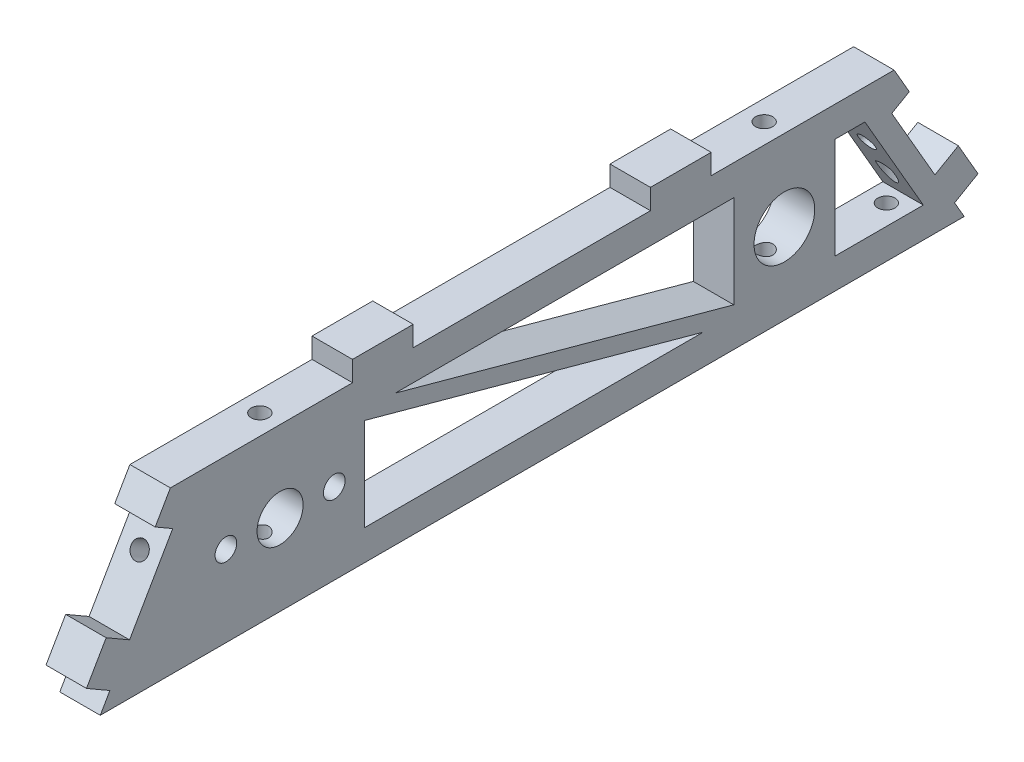
SolidWorks part; units mm, degrees
material "6061-T6 (SS)"
ref_plane "Front Plane" through (0, 0, 0) normal (0, 0, 1) x (1, 0, 0)
ref_plane "Top Plane" through (0, 0, 0) normal (0, 1, 0) x (1, 0, 0)
ref_plane "Right Plane" through (0, 0, 0) normal (1, 0, 0) x (0, 0, -1)
sketch "Sketch1" plane through (0, 0, 0) normal (1, 0, 0) x (0, 0, -1)
  line L0 (0, 0) -> (-14.6647, 25.4)
  line L1 (0, 0) -> (-142.875, 0)
  line L3 (-14.6647, 25.4) -> (-128.2103, 25.4)
  line L5 (-142.875, 0) -> (-128.2103, 25.4)
  circle A0 centre (-110.998, 12.7) radius 3.6195
  circle A1 centre (-31.877, 12.7) radius 4.7625
  circle A2 centre (-102.498, 12.7) radius 1.7
  circle A3 centre (-119.498, 12.7) radius 1.7
  dimension "D3" = 7.239
  dimension "D5" = 9.525
  dimension "D9" = 3.4
  dimension "D2" = 25.4
  dimension "D4" = 12.7
  dimension "D6" = 142.875
  dimension "D7" = 31.877
  dimension "D8" = 12.7
  dimension "D10" = 8.5
  dimension "D11" = 8.5
  dimension "D13" = 60
  dimension "D14" = 60
  dimension "D15" = 31.877
extrude "Boss-Extrude1" add sketch "Sketch1" along normal blind 6.35
sketch "Sketch12" plane through (0, 0, 0) normal (0, 0.5, -0.866) x (-1, 0, 0)
  line L0 (-6.35, 0) -> (-6.35, 29.3294) construction
  line L1 (-6.35, 11.0236) -> (0, 11.0236)
  line L2 (-6.35, 11.0236) -> (-6.35, 4.8514)
  line L3 (-6.35, 4.8514) -> (0, 4.8514)
  line L4 (0, 11.0236) -> (0, 4.8514)
  line L5 (0, 0) -> (0, 29.3294) construction
  line L6 (0, 7.9375) -> (-6.35, 7.9375) construction
  line L8 (-6.35, 0) -> (0, 0) construction
  point P8 (0, 7.9375)
  dimension "D1" = 6.1722
  dimension "D2" = 7.9375
extrude "Boss-Extrude3" add sketch "Sketch12" along normal blind 1.0668
sketch "Sketch19" plane through (0, 0, 0) normal (-1, 0, 0) x (0, 0, 1)
  line L0 (14.6647, 25.4) -> (128.2103, 25.4) construction
  line L1 (39.8145, 20.6375) -> (97.7355, 20.6375)
  line L2 (39.8145, 20.6375) -> (39.8145, 4.7625)
  line L3 (39.8145, 4.7625) -> (97.7355, 4.7625)
  line L4 (97.7355, 20.6375) -> (97.7355, 4.7625)
  line L5 (142.875, 0) -> (0, 0) construction
  line L6 (39.8145, 4.7625) -> (97.7355, 20.6375) construction
  line L7 (44.6191, 4.7625) -> (97.7355, 19.3207)
  line L8 (39.8145, 6.0793) -> (92.9309, 20.6375)
  line L9 (39.4788, 5.9873) -> (97.3998, 21.8623) construction
  line L10 (40.1502, 3.5377) -> (98.0712, 19.4127) construction
  line L11 (10.082, 4.7625) -> (19.2474, 20.6375)
  line L12 (23.9395, 20.6375) -> (23.9395, 4.7625)
  line L13 (23.9395, 4.7625) -> (10.082, 4.7625)
  line L14 (5.5118, 9.5467) -> (14.6647, 25.4) construction
  line L15 (23.9395, 20.6375) -> (19.2474, 20.6375)
  circle A0 centre (31.877, 12.7) radius 4.7625 construction
  circle A1 centre (102.498, 12.7) radius 1.7 construction
  dimension "D1" = 4.7625
  dimension "D2" = 4.7625
  dimension "D3" = 7.9375
  dimension "D4" = 4.7625
  dimension "D7" = 6.35
  dimension "D8" = 7.9375
  dimension "D9" = 4.7625
  dimension "D5" = 1.27
  dimension "D6" = 1.27
extrude "Cut-Extrude1" cut sketch "Sketch19" against normal through all contours L2 L8 L1 | L7 L3 L4 | L12 L15 L11 L13
hole_wizard "Tap Drill for #6-32 Tap4" positions "Sketch7" profile "Sketch6" hole size "#6-32" standard "ANSI Inch" end condition through all
sketch "Sketch7" plane through (0, 25.4, 0) normal (0, 1, 0) x (1, 0, 0)
  line L2 (0, -14.6647) -> (0, -128.2103) construction
  line L4 (6.35, -14.6647) -> (6.35, -128.2103) construction
  line L9 (6.35, -142.875) -> (0, -142.875) construction
  line L10 (6.35, 0) -> (0, 0) construction
  point P0 (3.175, -110.998)
  point P2 (3.175, -31.877)
  point P16 (3.175, -31.877)
  point P18 (3.175, -110.998)
  point P22 (3.175, -110.998)
  dimension "D1" = 31.877
  dimension "D2" = 31.877
  dimension "D3" = 3.175
  dimension "D4" = 3.175
sketch "Sketch6" plane through (3.175, 25.4, 110.998) normal (1, 0, 0) x (0, 0, 1)
  line L0 (0, 0) -> (0, 25.4)
  line L1 (0, 25.4) -> (1.3525, 25.4)
  line L2 (1.3525, 25.4) -> (1.3525, 0)
  line L5 (1.3525, 0) -> (0, 0)
  line L11 (0, -6.35) -> (0, 107.95) construction
  dimension "Thru Hole Dia." = 2.7051
  dimension "Thru Hole Depth" = 25.4
hole_wizard "Tap Drill for #6-32 Tap3" positions "Sketch9" profile "Sketch8" hole size "#6-32" standard "ANSI Inch"
sketch "Sketch9" plane through (0, 0, 0) normal (0, -1, 0) x (-1, 0, 0)
  line L1 (0, -142.875) -> (0, 0) construction
  line L3 (-6.35, 0) -> (0, 0) construction
  line L4 (-6.35, -142.875) -> (0, -142.875) construction
  point P0 (-3.175, -130.175)
  point P2 (-3.175, -12.7)
  dimension "D1" = 12.7
  dimension "D2" = 3.175
  dimension "D3" = 12.7
  dimension "D4" = 3.175
sketch "Sketch8" plane through (3.175, 0, 130.175) normal (1, 0, 0) x (0, 0, -1)
  line L0 (0, 0) -> (0, 10.9727)
  line L1 (0, 10.9727) -> (1.3525, 10.16)
  line L2 (1.3525, 10.16) -> (1.3525, 0)
  line L5 (1.3525, 0) -> (0, 0)
  line L10 (0, 10.9727) -> (-1.3526, 10.16) construction
  line L11 (0, -6.35) -> (0, 107.95) construction
  dimension "Hole Dia." = 2.7051
  dimension "Hole Depth" = 10.16
  dimension "Drill Angle" = 118
hole_wizard "Tap Drill for #6-32 Tap2" positions "Sketch16" profile "Sketch15" hole size "#6-32" standard "ANSI Inch"
sketch "Sketch16" plane through (0, 0, 0) normal (0, 0.5, -0.866) x (-1, 0, 0)
  line L2 (0, 0.8826) -> (-6.35, 0.8826) construction
  line L6 (0, 20.5486) -> (-6.35, 20.5486) construction
  line L9 (-3.175, 29.3294) -> (-3.175, 0) construction
  line L10 (-6.35, 29.3294) -> (0, 29.3294) construction
  line L11 (-6.35, 0) -> (0, 0) construction
  line L13 (-6.35, 4.8514) -> (0, 4.8514) construction
  line L14 (0, 11.0236) -> (-6.35, 11.0236) construction
  point P7 (-3.175, 20.5486)
  dimension "D1" = 3.9688
  dimension "D2" = 9.525
sketch "Sketch15" plane through (3.175, 17.7956, 10.2743) normal (1, 0, 0) x (0, 0.866, 0.5)
  line L0 (0, 0) -> (0, 8.4327)
  line L1 (0, 8.4327) -> (1.3525, 7.62)
  line L2 (1.3525, 7.62) -> (1.3525, 0)
  line L5 (1.3525, 0) -> (0, 0)
  line L10 (0, 8.4327) -> (-1.3525, 7.62) construction
  line L11 (0, -6.35) -> (0, 107.95) construction
  dimension "Hole Dia." = 2.7051
  dimension "Hole Depth" = 7.62
  dimension "Drill Angle" = 118
ref_plane "Plane1" through (0, 0, 71.4375) normal (0, 0, -1) x (-1, 0, 0)
sketch "Sketch20" plane through (0, 0, 0) normal (0, 0.5, -0.866) x (-1, 0, 0)
  line L0 (-6.35, 4.8514) -> (0, 4.8514) construction
  line L1 (-6.35, 24.5669) -> (0, 24.5669)
  line L2 (-6.35, 24.5669) -> (-6.35, 11.0236)
  line L3 (-6.35, 11.0236) -> (0, 11.0236)
  line L4 (0, 24.5669) -> (0, 11.0236)
  line L5 (-6.35, -7.8486) -> (0, -7.8486)
  line L6 (-6.35, -7.8486) -> (-6.35, 4.8514)
  line L7 (-6.35, 4.8514) -> (0, 4.8514)
  line L8 (0, -7.8486) -> (0, 4.8514)
  line L9 (0, 0) -> (0, 4.8514) construction
  line L10 (-6.35, 0) -> (-6.35, 4.8514) construction
  line L11 (-6.35, 11.0236) -> (-6.35, 29.3294) construction
  line L12 (-6.35, 29.3294) -> (0, 29.3294) construction
  line L13 (0, 11.0236) -> (-6.35, 11.0236) construction
  dimension "D1" = 12.7
  dimension "D3" = 4.7625
extrude "Cut-Extrude2" cut sketch "Sketch20" against normal blind 3.175
mirror "Mirror1" about plane through (0, 0, 71.4375) normal (0, 0, -1) of "Cut-Extrude2", "Tap Drill for #6-32 Tap2", "Boss-Extrude3"
sketch "Sketch21" plane through (0, 25.4, 0) normal (0, 1, 0) x (1, 0, 0)
  line L0 (0, -14.6647) -> (0, -128.2103) construction
  line L1 (0, -43.3667) -> (6.35, -43.3667)
  line L2 (0, -43.3667) -> (0, -52.8917)
  line L3 (0, -52.8917) -> (6.35, -52.8917)
  line L4 (6.35, -43.3667) -> (6.35, -52.8917)
  line L5 (6.35, -14.6647) -> (6.35, -128.2103) construction
  line L6 (6.35, -128.2103) -> (0, -128.2103) construction
  line L7 (6.35, -99.6353) -> (0, -99.6353)
  line L8 (6.35, -99.6353) -> (6.35, -90.1103)
  line L9 (6.35, -90.1103) -> (0, -90.1103)
  line L10 (0, -99.6353) -> (0, -90.1103)
  line L11 (6.35, -14.6647) -> (0, -14.6647) construction
  dimension "D1" = 28.575
  dimension "D2" = 9.525
  dimension "D3" = 28.702
extrude "Boss-Extrude4" add sketch "Sketch21" along normal blind 3.175
equation "\"D8@Sketch1\"=\"D4@Sketch1\""
equation "\"D11@Sketch1\"=\"D10@Sketch1\""
equation "\"D1@Sketch7\"=\"D2@Sketch7\""
